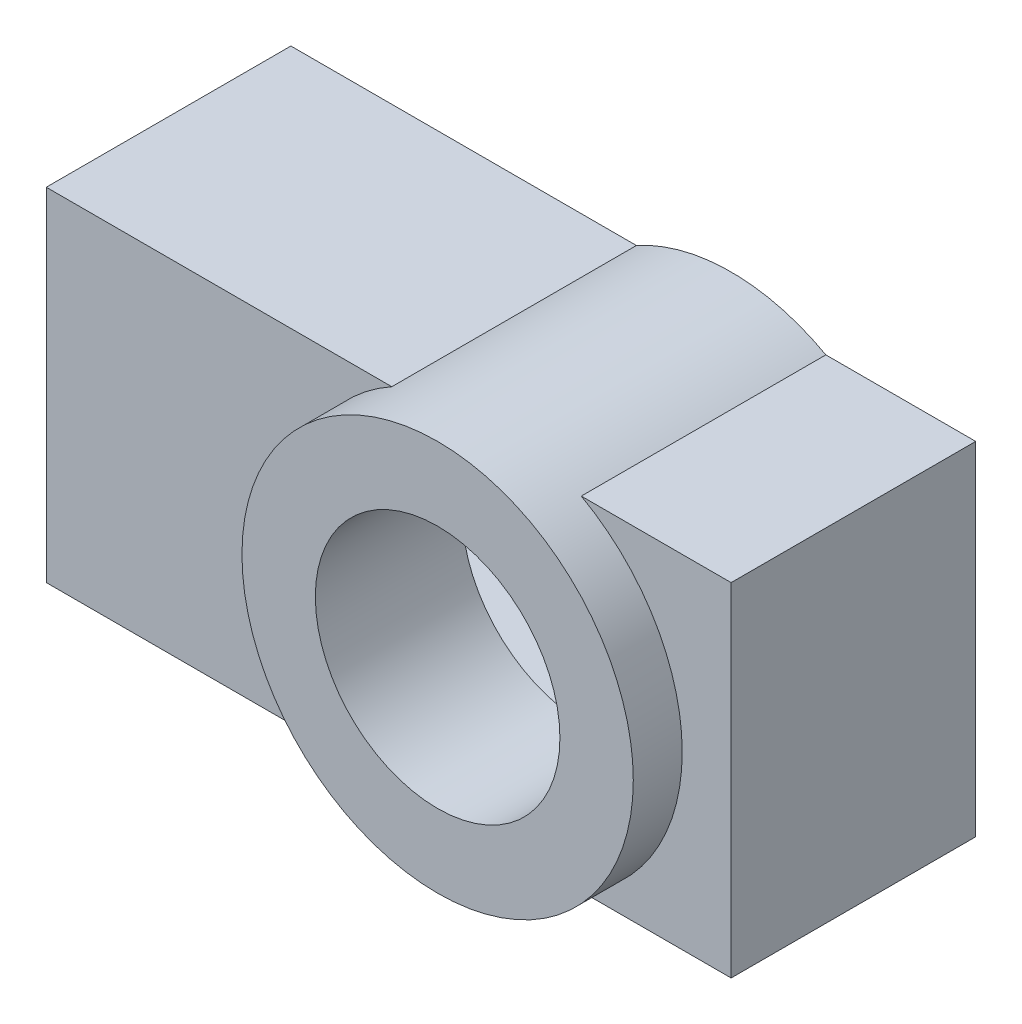
SolidWorks part; units mm, degrees
ref_plane "Front Plane" through (0, 0, 0) normal (0, 0, 1) x (1, 0, 0)
ref_plane "Top Plane" through (0, 0, 0) normal (0, 1, 0) x (1, 0, 0)
ref_plane "Right Plane" through (0, 0, 0) normal (1, 0, 0) x (0, 0, -1)
sketch "Sketch1" plane through (0, 0, 0) normal (1, 0, 0) x (0, 0, -1)
  line L1 (-1, -2.5) -> (1, -2.5)
  line L2 (-1, -2.5) -> (-1, 2.5)
  line L3 (-1, 2.5) -> (1, 2.5)
  line L4 (1, -2.5) -> (1, 2.5)
  line L5 (-1, -2.5) -> (1, 2.5) construction
  line L6 (-1, 2.5) -> (1, -2.5) construction
  line L7 (-2, -3.5) -> (2, -3.5)
  line L8 (-2, -3.5) -> (-2, 3.5)
  line L9 (-2, 3.5) -> (2, 3.5)
  line L10 (2, -3.5) -> (2, 3.5)
  line L11 (-2, -3.5) -> (2, 3.5) construction
  line L12 (-2, 3.5) -> (2, -3.5) construction
  line L13 (-2, 3.5) -> (-3, 3.5)
  line L14 (-2, 3.5) -> (-2, -3.5)
  line L15 (-2, -3.5) -> (-3, -3.5)
  line L16 (-3, 3.5) -> (-3, -3.5)
  point P0 (0, 0)
  point P6 (0, 0)
  dimension "D1" = 2
  dimension "D2" = 5
  dimension "D3" = 4
  dimension "D4" = 7
  dimension "D5" = 1
extrude "Boss-Extrude1" add sketch "Sketch1" along normal blind 14 contours L7 L10 L9 L8 L4 L1 L2 L3 | L13 L16 L15 L8
sketch "Sketch2" plane through (0, 0, 3) normal (0, 0, 1) x (1, 0, 0)
  line L0 (0, 0) -> (9, 0)
  line L1 (2.75, 0) -> (-2.75, 0) construction
  circle A0 centre (9, 0) radius 2.5
  circle A1 centre (9, 0) radius 4.5
  dimension "D2" = 5
  dimension "D3" = 9
  dimension "D1" = 9
extrude "Cut-Extrude1" cut sketch "Sketch2" against normal blind 14
sketch "Sketch3" plane through (0, 0, 3) normal (0, 0, 1) x (1, 0, 0)
  circle A0 centre (9, 0) radius 4
  circle A1 centre (9, 0) radius 2.5
  dimension "D1" = 8
extrude "Boss-Extrude3" add sketch "Sketch3" along normal blind 1 and the other way blind 5
sketch "Sketch4" plane through (14, 0, 0) normal (1, 0, 0) x (0, 0, -1)
  line L1 (-1, 2.5) -> (1, 2.5)
  line L2 (-1, 2.5) -> (-1, -2.5)
  line L3 (-1, -2.5) -> (1, -2.5)
  line L4 (1, 2.5) -> (1, -2.5)
extrude "Cut-Extrude2" cut sketch "Sketch4" against normal through all
sketch "Sketch6" plane through (0, 0, -2) normal (0, 0, -1) x (-1, 0, 0)
  line L1 (-12.0264, 2.7276) -> (-6.0508, 2.7276)
  line L2 (-12.0264, 2.7276) -> (-12.0264, -2.7109)
  line L3 (-12.0264, -2.7109) -> (-6.0508, -2.7109)
  line L4 (-6.0508, 2.7276) -> (-6.0508, -2.7109)
extrude "Boss-Extrude4" add sketch "Sketch6" against normal blind 0.5
sketch "Sketch7" plane through (14, 0, 0) normal (1, 0, 0) x (0, 0, -1)
  line L1 (-1, 2.5) -> (1, 2.5)
  line L2 (-1, 2.5) -> (-1, -2.5)
  line L3 (-1, -2.5) -> (1, -2.5)
  line L4 (1, 2.5) -> (1, -2.5)
extrude "Boss-Extrude5" add sketch "Sketch7" against normal blind 2
